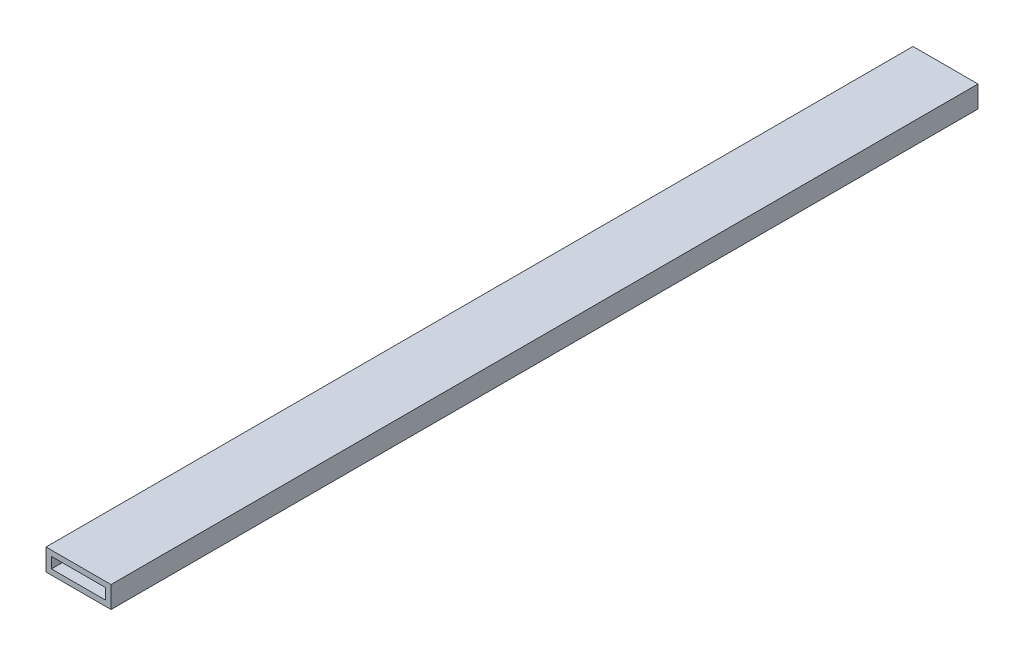
SolidWorks part; units mm, degrees
material "6061-T6 (SS)"
ref_plane "Front" through (0, 0, 0) normal (0, 0, 1) x (1, 0, 0)
ref_plane "Top" through (0, 0, 0) normal (0, 1, 0) x (1, 0, 0)
ref_plane "Right" through (0, 0, 0) normal (1, 0, 0) x (0, 0, -1)
sketch "Sketch1" plane through (0, 0, 0) normal (0, 0, 1) x (1, 0, 0)
  line L0 (-12.5, -2.5) -> (-12.5, 2.5)
  line L1 (-15, -5) -> (15, -5)
  line L2 (-15, -5) -> (-15, 5)
  line L3 (-15, 5) -> (15, 5)
  line L4 (15, -5) -> (15, 5)
  line L5 (-15, -5) -> (15, 5) construction
  line L6 (-15, 5) -> (15, -5) construction
  line L7 (-12.5, 2.5) -> (12.5, 2.5)
  line L8 (12.5, -2.5) -> (12.5, 2.5)
  line L9 (-12.5, -2.5) -> (12.5, -2.5)
  point P0 (0, 0)
  dimension "D2" = 30
  dimension "D3" = 10
  dimension "D1" = 2.5
extrude "Boss-Extrude1" add sketch "Sketch1" along normal mid plane 400
